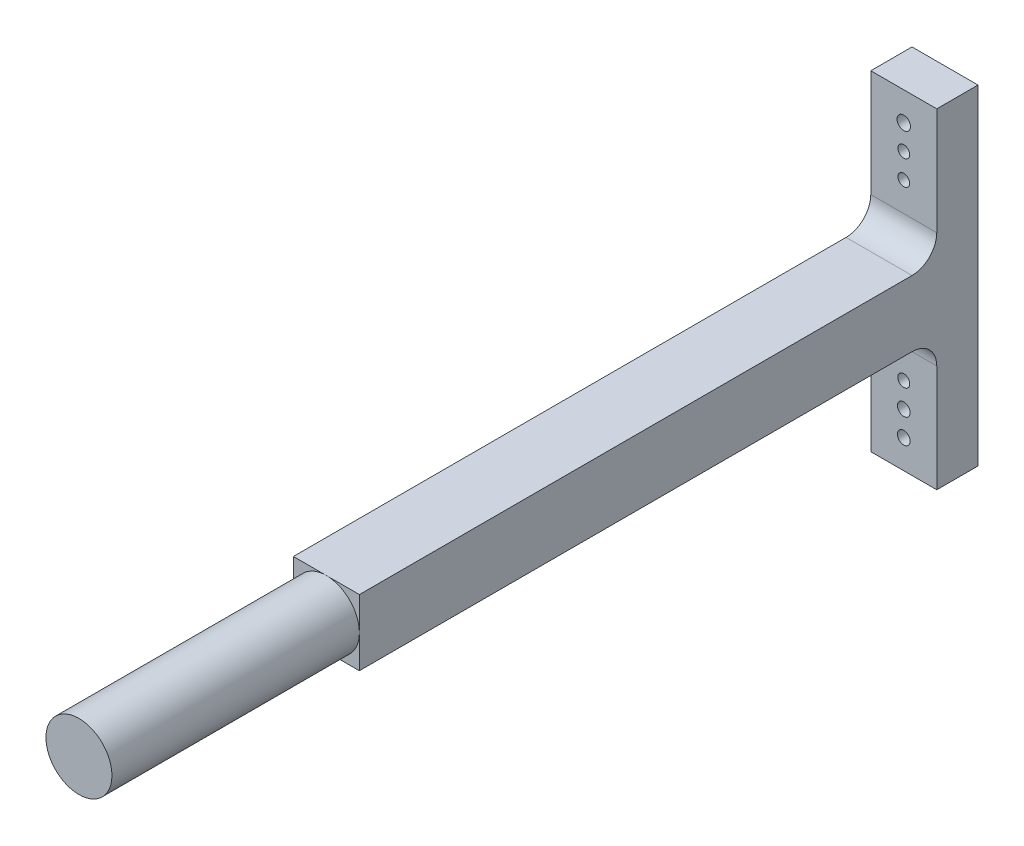
SolidWorks part; units mm, degrees
ref_plane "Ön Düzlem" through (0, 0, 0) normal (0, 0, 1) x (1, 0, 0)
ref_plane "Üst Düzlem" through (0, 0, 0) normal (0, 1, 0) x (1, 0, 0)
ref_plane "Sağ Düzlem" through (0, 0, 0) normal (1, 0, 0) x (0, 0, -1)
sketch "Sketch1" plane through (0, 0, 0) normal (0, 0, 1) x (1, 0, 0)
  line L1 (0, 0) -> (8, 0)
  line L2 (0, 0) -> (0, 40)
  line L3 (0, 40) -> (8, 40)
  line L4 (8, 0) -> (8, 40)
  dimension "D1" = 40
  dimension "D2" = 8
extrude "Boss-Extrude1" add sketch "Sketch1" along normal blind 5
sketch "Sketch3" plane through (0, 0, 5) normal (0, 0, 1) x (1, 0, 0)
  line L0 (0, 40) -> (0, 0) construction
  line L1 (0, 24) -> (8, 24)
  line L2 (0, 24) -> (0, 16)
  line L3 (0, 16) -> (8, 16)
  line L4 (8, 24) -> (8, 16)
  line L5 (8, 0) -> (8, 40) construction
  point P7 (0, 20)
  point P8 (0, 20)
  dimension "D1" = 8
extrude "Boss-Extrude3" add sketch "Sketch3" along normal blind 70
sketch "Sketch4" plane through (0, 0, 75) normal (0, 0, 1) x (1, 0, 0)
  line L0 (0, 24) -> (0, 16) construction
  line L1 (8, 24) -> (0, 24) construction
  line L2 (0, 16) -> (8, 16) construction
  circle A0 centre (4, 20) radius 4
  point P5 (0, 20)
  point P9 (4, 24)
extrude "Boss-Extrude4" add sketch "Sketch4" along normal blind 30
sketch "Sketch5" plane through (0, 0, 5) normal (0, 0, 1) x (1, 0, 0)
  circle A0 centre (4, 3.47) radius 0.7736
  circle A1 centre (4, 6.47) radius 0.7683
  circle A2 centre (4, 9.47) radius 0.7265
  circle A3 centre (4, 30.53) radius 0.7072
  circle A4 centre (4, 33.53) radius 0.7159
  circle A5 centre (4, 36.53) radius 0.8126
extrude "Cut-Extrude1" cut sketch "Sketch5" against normal blind 10
fillet "Fillet1" radius 3 2 edges at (4, 16, 5) (4, 24, 5)
